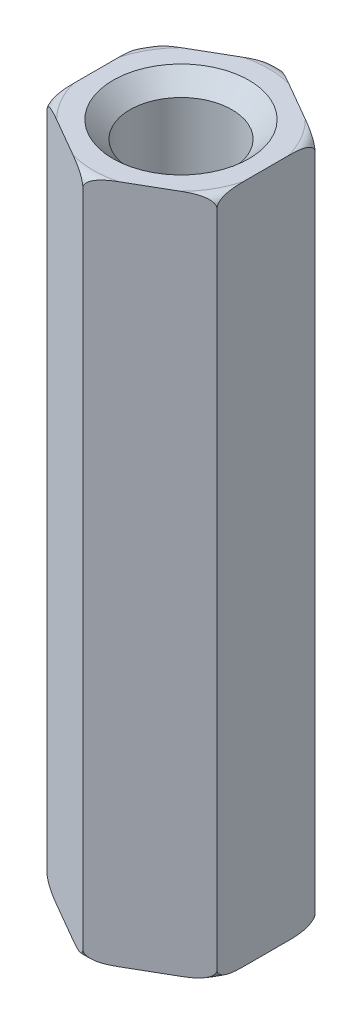
SolidWorks part; units mm, degrees
ref_plane "Front Plane" through (0, 0, 0) normal (0, 0, 1) x (1, 0, 0)
ref_plane "Top Plane" through (0, 0, 0) normal (0, 1, 0) x (1, 0, 0)
ref_plane "Right Plane" through (0, 0, 0) normal (1, 0, 0) x (0, 0, -1)
sketch "Sketch2" plane through (0, 0, 0) normal (0, 1, 0) x (1, 0, 0)
  line L1 (0, -2.8868) -> (2.5, -1.4434)
  line L2 (2.5, -1.4434) -> (2.5, 1.4434)
  line L3 (2.5, 1.4434) -> (0, 2.8868)
  line L4 (0, 2.8868) -> (-2.5, 1.4434)
  line L5 (-2.5, 1.4434) -> (-2.5, -1.4434)
  line L6 (-2.5, -1.4434) -> (0, -2.8868)
  circle A0 centre (0, 0) radius 2.5 construction
  circle A1 centre (0, 0) radius 1.5
  dimension "D1" = 3
  dimension "D2" = 5
extrude "Boss-Extrude2" add sketch "Sketch2" along normal mid plane 20 contours A1
chamfer "Chamfer1" distance 0.5 angle 45 2 edges at (0, -10, 1.5) (0, 10, 1.5)
sketch "Sketch4" plane through (0, 0, 0) normal (1, 0, 0) x (0, 0, -1)
  line L1 (-2.8868, 10) -> (-2.8868, -10) construction
  line L3 (-2.8868, 10) -> (-1.4434, 10) construction
  line L4 (-2.8868, 9.7) -> (-2.8868, 10)
  line L5 (-2.8868, 10) -> (-2.5868, 10)
  arc A0 (-2.8868, 9.7) -> (-2.5868, 10) centre (-2.5868, 9.7) cw
  dimension "D1" = 0.3
ref_axis "Axis1" through (0, 57.75, 0) along (0, -1, 0)
revolve "Cut-Revolve1" cut sketch "Sketch4" angle 360 about axis through (0, 57.75, 0) along (0, -1, 0)
mirror "Mirror1" about plane through (0, 0, 0) normal (0, 1, 0) of "Cut-Revolve1"
